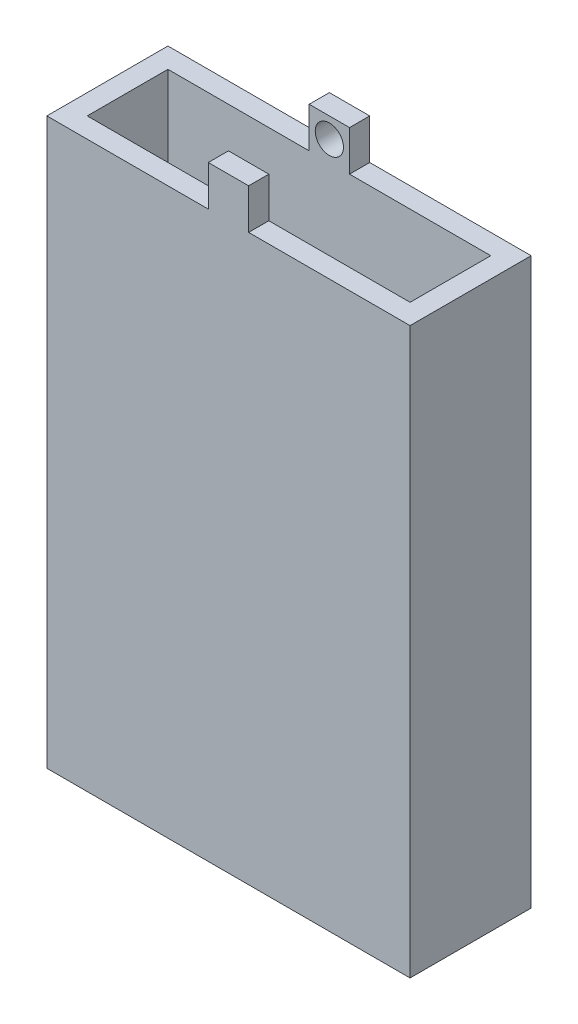
SolidWorks part; units mm, degrees
ref_plane "Front Plane" through (0, 0, 0) normal (0, 0, 1) x (1, 0, 0)
ref_plane "Top Plane" through (0, 0, 0) normal (0, 1, 0) x (1, 0, 0)
ref_plane "Right Plane" through (0, 0, 0) normal (1, 0, 0) x (0, 0, -1)
sketch "Sketch1" plane through (0, 0, 0) normal (0, 1, 0) x (1, 0, 0)
  line L0 (-47.788, -11.1577) -> (42.212, -11.1577) construction
  line L1 (42.212, -26.1577) -> (-47.788, -26.1577)
  line L2 (42.212, -26.1577) -> (42.212, 3.8423)
  line L3 (42.212, 3.8423) -> (-47.788, 3.8423)
  line L4 (-47.788, -26.1577) -> (-47.788, 3.8423)
  line L5 (-47.788, -11.1577) -> (-42.788, -11.1577) construction
  line L6 (42.212, -11.1577) -> (37.212, -11.1577) construction
  line L7 (-2.788, 3.8423) -> (-2.788, -26.1577) construction
  line L8 (-2.788, -26.1577) -> (-2.788, -21.1577) construction
  line L9 (-2.788, 3.8423) -> (-2.788, -1.1577) construction
extrude "Boss-Extrude1" add sketch "Sketch1" along normal blind 140
sketch "Sketch2" plane through (0, 140, 0) normal (0, 1, 0) x (1, 0, 0)
  line L0 (-47.788, -11.1577) -> (42.212, -11.1577) construction
  line L1 (-47.788, 3.8423) -> (-47.788, -26.1577) construction
  line L2 (42.212, -26.1577) -> (42.212, 3.8423) construction
  line L3 (-2.788, 3.8423) -> (-2.788, -26.1577) construction
  line L4 (42.212, 3.8423) -> (-47.788, 3.8423) construction
  line L5 (-47.788, -26.1577) -> (42.212, -26.1577) construction
  line L6 (-47.788, -11.1577) -> (-42.788, -11.1577) construction
  line L7 (-2.788, 3.8423) -> (-2.788, -1.1577) construction
  line L8 (-2.788, -26.1577) -> (-2.788, -21.1577) construction
  line L9 (42.212, -11.1577) -> (37.212, -11.1577) construction
  line L11 (-42.788, -1.1577) -> (37.212, -1.1577)
  line L12 (-42.788, -1.1577) -> (-42.788, -21.1577)
  line L13 (-42.788, -21.1577) -> (37.212, -21.1577)
  line L14 (37.212, -1.1577) -> (37.212, -21.1577)
extrude "Cut-Extrude1" cut sketch "Sketch2" against normal blind 135
sketch "Sketch4" plane through (0, 140, 0) normal (0, 1, 0) x (1, 0, 0)
  line L0 (-47.788, -11.1577) -> (42.212, -11.1577) construction
  line L1 (-47.788, 3.8423) -> (-47.788, -26.1577) construction
  line L2 (42.212, -26.1577) -> (42.212, 3.8423) construction
  line L3 (-2.788, 3.8423) -> (-2.788, -26.1577) construction
  line L4 (42.212, 3.8423) -> (-47.788, 3.8423) construction
  line L5 (-47.788, -26.1577) -> (42.212, -26.1577) construction
  line L6 (-7.788, 1.2244) -> (2.212, 1.2244) construction
  line L8 (-7.788, 3.8423) -> (2.212, 3.8423)
  line L9 (-7.788, 3.8423) -> (-7.788, -26.1577)
  line L10 (-7.788, -26.1577) -> (2.212, -26.1577)
  line L11 (2.212, 3.8423) -> (2.212, -26.1577)
  point P15 (-2.788, 1.2244)
extrude "Boss-Extrude2" add sketch "Sketch4" along normal blind 10
sketch "Sketch5" plane through (0, 0, -3.8423) normal (0, 0, -1) x (-1, 0, 0)
  line L0 (-2.212, 145) -> (7.788, 145) construction
  line L1 (-2.212, 150) -> (-2.212, 140) construction
  line L2 (7.788, 150) -> (7.788, 140) construction
  line L3 (2.788, 150) -> (2.788, 145) construction
  line L4 (-2.212, 150) -> (7.788, 150) construction
  circle A0 centre (2.788, 145) radius 3.5
sketch "Sketch7" plane through (2.212, 0, 0) normal (1, 0, 0) x (0, 0, -1)
  line L0 (-26.1577, 144.7906) -> (-21.1577, 144.7906) construction
  line L1 (-26.1577, 150) -> (-26.1577, 140) construction
  line L2 (3.8423, 144.5814) -> (-1.1577, 144.5814) construction
  line L3 (3.8423, 150) -> (3.8423, 140) construction
  line L4 (-26.1577, 150) -> (3.8423, 150) construction
  line L5 (-21.1577, 150) -> (-1.1577, 150)
  line L6 (-21.1577, 150) -> (-21.1577, 140)
  line L7 (-21.1577, 140) -> (-1.1577, 140)
  line L8 (-1.1577, 150) -> (-1.1577, 140)
extrude "Cut-Extrude3" cut sketch "Sketch7" against normal blind 10
extrude "Cut-Extrude4" cut sketch "Sketch5" against normal blind 27.5
